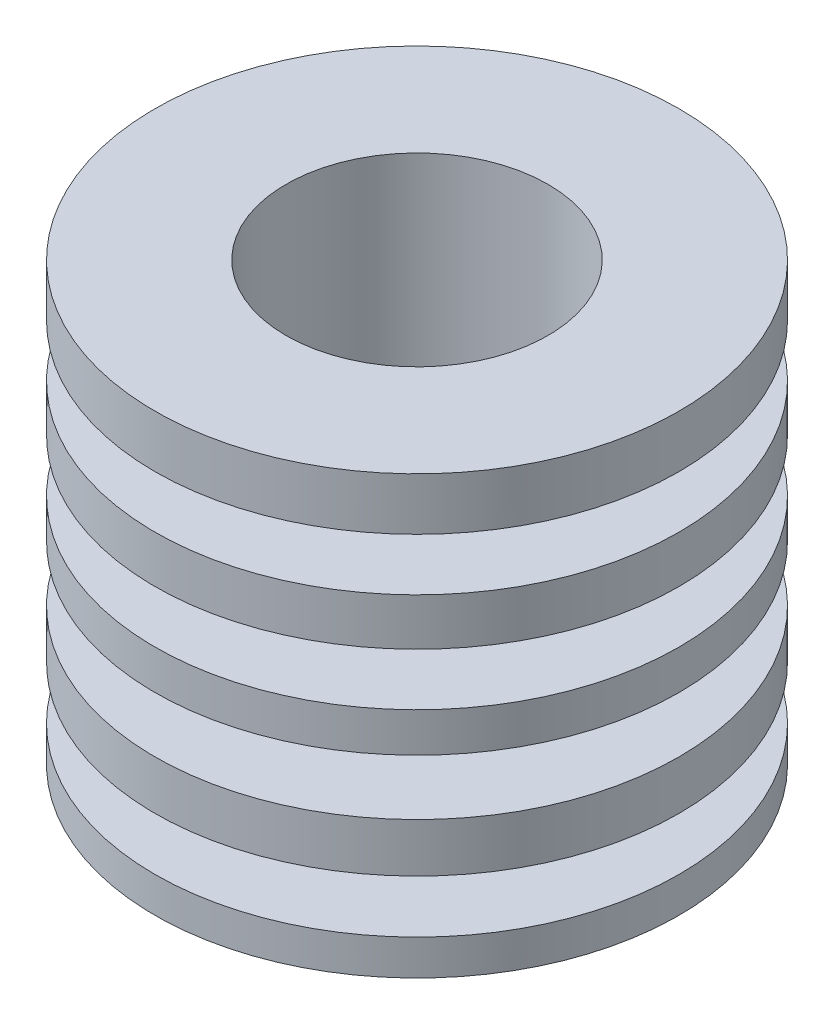
SolidWorks part; units mm, degrees
ref_plane "Front Plane" through (0, 0, 0) normal (0, 0, 1) x (1, 0, 0)
ref_plane "Top Plane" through (0, 0, 0) normal (0, 1, 0) x (1, 0, 0)
ref_plane "Right Plane" through (0, 0, 0) normal (1, 0, 0) x (0, 0, -1)
sketch "Sketch1" plane through (0, 0, 0) normal (0, 0, 1) x (1, 0, 0)
  line L0 (0, 0) -> (0, 139.0858) construction
  line L2 (-75, 0) -> (-150, 0)
  line L3 (-75, 0) -> (-75, 250)
  line L4 (-75, 250) -> (-150, 250)
  line L5 (-150, 0) -> (-150, 250)
  dimension "D1" = 150
  dimension "D2" = 300
  dimension "D3" = 250
revolve "Revolve1" add sketch "Sketch1" angle 360 about L0
sketch "Sketch2" plane through (0, 0, 0) normal (0, 0, 1) x (1, 0, 0)
  line L0 (0, 0) -> (0, 139.0858) construction
  line L1 (0, 0) -> (0, 261.1039) construction
  line L2 (-150, 250) -> (-150, 0) construction
  line L3 (-150, 220) -> (-80.0301, 220)
  line L4 (-150, 220) -> (-150, 190)
  line L5 (-150, 190) -> (-80.0301, 190)
  line L6 (-80.0301, 220) -> (-80.0301, 190)
  line L7 (150, 250) -> (-150, 250) construction
  line L9 (-150, 163.0265) -> (-80.0301, 163.0265)
  line L10 (-150, 163.0265) -> (-150, 133.0265)
  line L11 (-150, 133.0265) -> (-80.0301, 133.0265)
  line L12 (-80.0301, 163.0265) -> (-80.0301, 133.0265)
  line L13 (-150, 110.4806) -> (-80.0301, 110.4806)
  line L14 (-150, 110.4806) -> (-150, 78.5864)
  line L15 (-150, 78.5864) -> (-80.0301, 78.5864)
  line L16 (-80.0301, 110.4806) -> (-80.0301, 78.5864)
  line L17 (-150, 50.5416) -> (-80.0301, 50.5416)
  line L18 (-150, 50.5416) -> (-150, 20.2971)
  line L19 (-150, 20.2971) -> (-80.0301, 20.2971)
  line L20 (-80.0301, 50.5416) -> (-80.0301, 20.2971)
  dimension "D1" = 80.0301
  dimension "D2" = 30
  dimension "D3" = 30
  dimension "D4" = 30
  dimension "D5" = 30
  dimension "D6" = 30
  dimension "D7" = 31.8942
  dimension "D8" = 30.2445
revolve "Cut-Revolve2" cut sketch "Sketch2" angle 360 about L1
